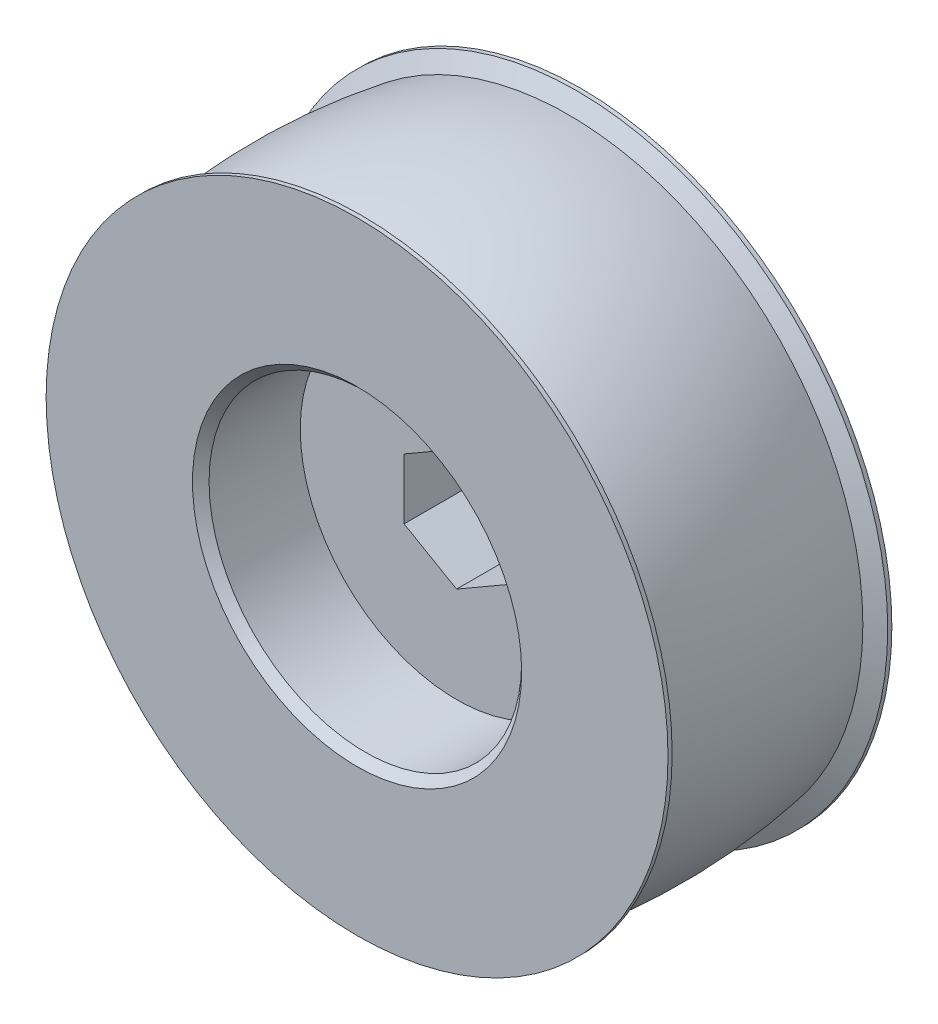
SolidWorks part; units mm, degrees
ref_plane "Plan de face" through (0, 0, 0) normal (0, 0, 1) x (1, 0, 0)
ref_plane "Plan de dessus" through (0, 0, 0) normal (0, 1, 0) x (1, 0, 0)
ref_plane "Plan de droite" through (0, 0, 0) normal (1, 0, 0) x (0, 0, -1)
sketch "Esquisse1" plane through (0, 0, 0) normal (0, 0, 1) x (1, 0, 0)
  circle A0 centre (0, 0) radius 2.15
  circle A1 centre (0, 0) radius 37.5
  dimension "D1" = 75
  dimension "D2" = 4.3
extrude "Boss.-Extru.1" add sketch "Esquisse1" along normal blind 15
sketch "Esquisse2" plane through (0, 0, 15) normal (0, 0, 1) x (1, 0, 0)
  circle A0 centre (0, 0) radius 37.5
  circle A1 centre (0, 0) radius 18.85
  circle A2 centre (0, 0) radius 37.5 construction
  dimension "D1" = 37.7
extrude "Boss.-Extru.2" add sketch "Esquisse2" along normal blind 12
sketch "Esquisse9" plane through (0, 0, 15) normal (0, 0, 1) x (1, 0, 0)
  line L0 (0, 0) -> (0, 14.607) construction
  line L1 (6.325, -3.6517) -> (6.325, 3.6517)
  line L2 (6.325, 3.6517) -> (0, 7.3035)
  line L3 (0, 7.3035) -> (-6.325, 3.6517)
  line L4 (-6.325, 3.6517) -> (-6.325, -3.6517)
  line L5 (-6.325, -3.6517) -> (0, -7.3035)
  line L6 (0, -7.3035) -> (6.325, -3.6517)
  circle A0 centre (0, 0) radius 6.325 construction
  dimension "D1" = 12.65
extrude "Enlèv. mat.-Extru.9" cut sketch "Esquisse9" against normal offset from surface (13 mm away) 2 up to face at (37.5, 0, 0)
chamfer "Chanfrein1" distance 1 angle 45 1 edges at (18.85, 0, 27)
sketch "Esquisse10" plane through (0, 0, 0) normal (1, 0, 0) x (0, 0, -1)
  line L0 (-26.5, 37.5) -> (-0.5, 37.5)
  line L1 (0, 37.5) -> (-27, 37.5) construction
  line L2 (-0.5, 37.5) -> (-1.5, 35.5)
  line L3 (-1.5, 35.5) -> (-25.5, 35.5) construction
  line L4 (-25.5, 35.5) -> (-26.5, 37.5)
  line L5 (-19.6787, 36.5) -> (-7.7815, 36.5) construction
  line L6 (0, 0) -> (-50.6564, 0) construction
  arc A0 (-25.5, 35.5) -> (-1.5, 35.5) centre (-13.5, -36) cw
  dimension "D6" = 1
  dimension "D1" = 2
  dimension "D2" = 0.5
  dimension "D3" = 0.5
  dimension "D4" = 1
  dimension "D5" = 1
revolve "Enlèvement de matière-Révolution1" cut sketch "Esquisse10" angle 360 about L6
